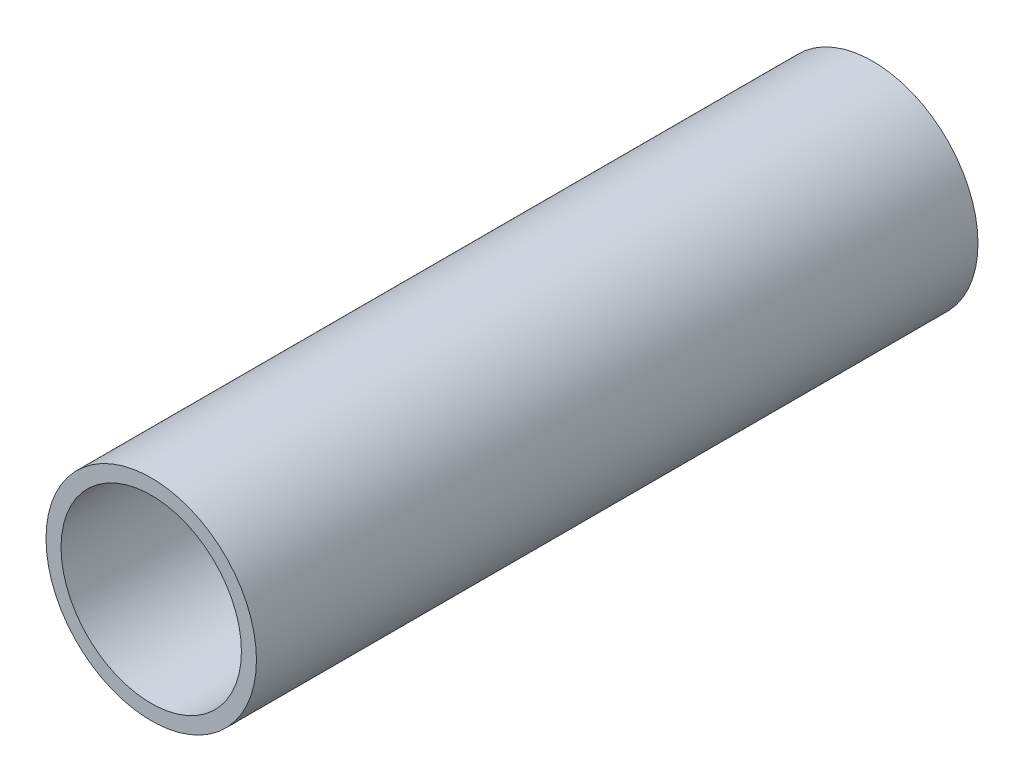
SolidWorks part; units mm, degrees
material "Alloy Steel"
ref_plane "Front Plane" through (0, 0, 0) normal (0, 0, 1) x (1, 0, 0)
ref_plane "Top Plane" through (0, 0, 0) normal (0, 1, 0) x (1, 0, 0)
ref_plane "Right Plane" through (0, 0, 0) normal (1, 0, 0) x (0, 0, -1)
sketch "Sketch1" plane through (0, 0, 0) normal (0, 0, 1) x (1, 0, 0)
  circle A0 centre (0, 0) radius 44.45
  circle A1 centre (0, 0) radius 38.1
  dimension "D1" = 88.9
  dimension "D2" = 6.35
extrude "Boss-Extrude1" add sketch "Sketch1" along normal blind 304.8
equation "\"delta-z\" = 1.5"
equation "\"max-tube-diam\" = 3.5"
equation "\"v-block-notch-height\" = 1.5"
equation "\"v-block-notch-angle\" = 120"
equation "\"vise-mod-plate-thickness\"= .375"
equation "\"vise-mod-height\"= .5 * \"max-tube-diam\" + \"delta-z\""
equation "\"jaw-travel\" = 4.45"
equation "\"D1@Sketch1\"=\"max-tube-diam\""
equation "\"total-height\" = 3.28"
equation "\"mid-height\" = 1.5"
equation "\"jaw-width\" = 4"
equation "\"jaw-height\" = \"total-height\" - \"mid-height\""
equation "\"rib-top-width\" = 0.5"
equation "\"rib-side-width\" = 0.5"
equation "\"quarter-twenty-close-clearance\" = .257"
equation "\"box-way-width\" = 1.5"
equation "\"box-way-depth\" = 1.5"
equation "\"screw-OD\" = .625"
equation "\"screw-reduced-diam\" = .47"
equation "\"pressure-plate-OD\" = 6.75"
equation "\"swivel-cleat-thick\" = .5"
equation "\"swivel-gap\" = .02"
